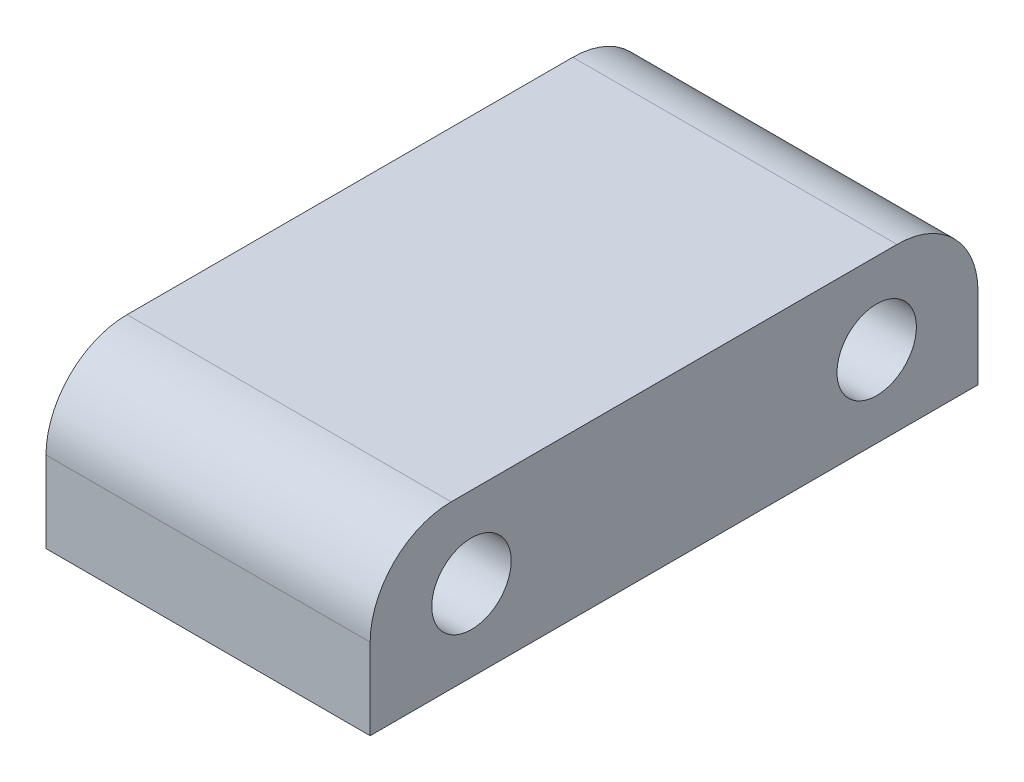
SolidWorks part; units mm, degrees
ref_plane "Front Plane" through (0, 0, 0) normal (0, 0, 1) x (1, 0, 0)
ref_plane "Top Plane" through (0, 0, 0) normal (0, 1, 0) x (1, 0, 0)
ref_plane "Right Plane" through (0, 0, 0) normal (1, 0, 0) x (0, 0, -1)
sketch "Sketch1" plane through (0, 0, 0) normal (1, 0, 0) x (0, 0, -1)
  line L0 (-25, 0) -> (25, 0) construction
  line L2 (-37.5, -10) -> (37.5, -10)
  line L3 (-37.5, -10) -> (-37.5, 10)
  line L4 (-37.5, 10) -> (37.5, 10)
  line L5 (37.5, -10) -> (37.5, 10)
  line L6 (-37.5, -10) -> (37.5, 10) construction
  line L7 (-37.5, 10) -> (37.5, -10) construction
  circle A0 centre (-25, 0) radius 4.9
  circle A1 centre (25, 0) radius 4.9
  point P4 (0, 0)
  point P7 (0, 0)
  dimension "D3" = 9.8
  dimension "D1" = 50
  dimension "D4" = 20
  dimension "D5" = 75
extrude "Boss-Extrude1" add sketch "Sketch1" along normal mid plane 40
fillet "Fillet1" radius 10 2 edges at (0, 10, -37.5) (0, 10, 37.5)
